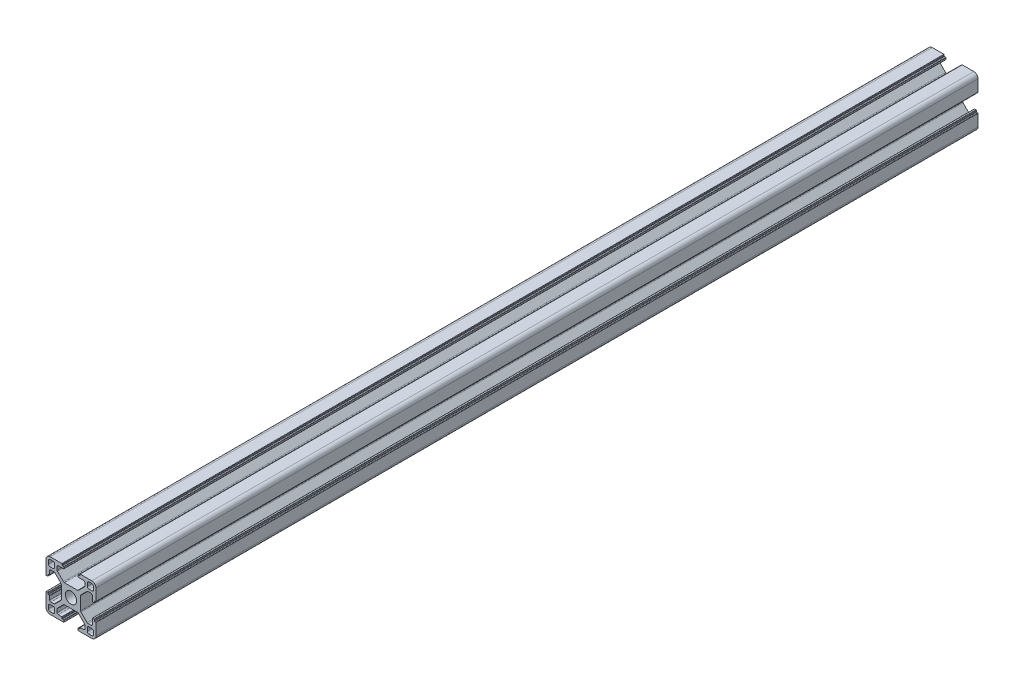
SolidWorks part; units mm, degrees
material "6063-T5"
ref_plane "Front Plane" through (0, 0, 0) normal (0, 0, 1) x (1, 0, 0)
ref_plane "Top Plane" through (0, 0, 0) normal (0, 1, 0) x (1, 0, 0)
ref_plane "Right Plane" through (0, 0, 0) normal (1, 0, 0) x (0, 0, -1)
sketch "Sketch1" plane through (0, 0, 0) normal (0, 0, 1) x (1, 0, 0)
  line L0 (0, 2.5) -> (0, 10.6)
  line L1 (2.5, 30) -> (9.5, 30)
  line L2 (30, 27.5) -> (30, 20.5)
  line L3 (27.5, 0) -> (19.4, 0)
  line L4 (19.464, 9.1128) -> (23.1303, 5.4465)
  line L5 (21.0197, 10.536) -> (24.686, 6.8697)
  line L6 (10.536, 21.0197) -> (6.8697, 24.686)
  line L7 (8.9803, 19.464) -> (5.314, 23.1303)
  line L8 (11.0663, 20.8) -> (18.9337, 20.8)
  line L9 (20.8, 18.9337) -> (20.8, 11.0663)
  line L10 (18.9337, 9.3324) -> (11.0663, 9.3324)
  line L11 (9.2, 11.0663) -> (9.2, 18.9337)
  line L12 (0, 19.4) -> (0, 27.5)
  line L13 (30, 9.5) -> (30, 2.5)
  line L14 (19.4, 27.8) -> (22.6, 27.8)
  line L15 (10.6, 27.8) -> (7.4, 27.8)
  line L16 (10.6, 0) -> (2.5, 0)
  line L17 (2.2, 20.5) -> (2.2, 22.6)
  line L18 (2.2, 9.5) -> (2.2, 7.4)
  line L19 (9.5, 2.3324) -> (7.4, 2.3324)
  line L20 (19.464, 21.0197) -> (23.1303, 24.686)
  line L21 (21.0197, 19.464) -> (24.686, 23.1303)
  line L22 (8.9803, 10.536) -> (5.314, 6.8697)
  line L23 (10.536, 9.1128) -> (6.8697, 5.4465)
  line L24 (10.8, 28.8) -> (10.8, 28)
  line L25 (19.2, 28.8) -> (19.2, 28)
  line L26 (0.2, 19.2) -> (1, 19.2)
  line L27 (0.2, 10.8) -> (1, 10.8)
  line L28 (28.8, 19.2) -> (28, 19.2)
  line L29 (28.8, 10.8) -> (28, 10.8)
  line L30 (10.8, 0.2) -> (10.8, 1.1324)
  line L31 (19.2, 0.2) -> (19.2, 1.1324)
  line L32 (20.5, 30) -> (27.5, 30)
  line L33 (27.8, 19.4) -> (27.8, 22.6)
  line L34 (27.8, 10.6) -> (27.8, 7.4)
  line L35 (20.5, 2.2) -> (22.6, 2.2)
  line L36 (6.65, 27.05) -> (6.65, 25.2163)
  line L37 (23.35, 27.05) -> (23.35, 25.2163)
  line L38 (2.95, 23.35) -> (4.7837, 23.35)
  line L39 (27.05, 23.35) -> (25.2163, 23.35)
  line L40 (2.95, 6.65) -> (4.7837, 6.65)
  line L41 (6.65, 3.0824) -> (6.65, 4.9161)
  line L42 (23.35, 2.95) -> (23.35, 4.9161)
  line L43 (27.05, 6.65) -> (25.2163, 6.65)
  line L44 (29, 10.6) -> (29, 9.9)
  line L45 (29.8, 20.3) -> (29.2, 20.3)
  line L46 (29, 20.1) -> (29, 19.4)
  line L47 (29.2, 9.7) -> (29.8, 9.7)
  line L48 (19.4, 29) -> (20.1, 29)
  line L49 (9.7, 29.8) -> (9.7, 29.2)
  line L50 (9.9, 29) -> (10.6, 29)
  line L51 (20.3, 29.2) -> (20.3, 29.8)
  line L52 (9.7, 2.1324) -> (9.7, 1.5324)
  line L53 (9.9, 1.3324) -> (10.6, 1.3324)
  line L54 (19.4, 1.3324) -> (20.1, 1.3324)
  line L55 (20.3, 1.5324) -> (20.3, 2)
  line L56 (2, 20.3) -> (1.4, 20.3)
  line L57 (1.2, 20.1) -> (1.2, 19.4)
  line L58 (1.2, 10.6) -> (1.2, 9.9)
  line L59 (1.4, 9.7) -> (2, 9.7)
  line L60 (27.55, 1.45) -> (25.8, 1.45)
  line L61 (24.8, 2.45) -> (24.8, 4.2)
  line L62 (25.8, 5.2) -> (27.55, 5.2)
  line L63 (28.55, 4.2) -> (28.55, 2.45)
  line L64 (24.8, 25.8) -> (24.8, 27.55)
  line L65 (25.8, 28.55) -> (27.55, 28.55)
  line L66 (28.55, 27.55) -> (28.55, 25.8)
  line L67 (27.55, 24.8) -> (25.8, 24.8)
  line L68 (2.45, 28.55) -> (4.2, 28.55)
  line L69 (5.2, 27.55) -> (5.2, 25.8)
  line L70 (1.45, 2.45) -> (1.45, 4.2)
  line L71 (2.45, 5.2) -> (4.2, 5.2)
  line L72 (5.2, 4.2) -> (5.2, 2.45)
  line L73 (4.2, 1.45) -> (2.45, 1.45)
  line L74 (4.2, 24.8) -> (2.45, 24.8)
  line L75 (1.45, 25.8) -> (1.45, 27.55)
  circle A0 centre (15, 15) radius 3.4
  arc A1 (25.8, 1.45) -> (24.8, 2.45) centre (25.8, 2.45) cw
  arc A2 (27.55, 1.45) -> (28.55, 2.45) centre (27.55, 2.45) ccw
  arc A3 (27.55, 5.2) -> (28.55, 4.2) centre (27.55, 4.2) cw
  arc A4 (24.8, 4.2) -> (25.8, 5.2) centre (25.8, 4.2) cw
  arc A5 (1.45, 2.45) -> (2.45, 1.45) centre (2.45, 2.45) ccw
  arc A6 (5.2, 2.45) -> (4.2, 1.45) centre (4.2, 2.45) cw
  arc A7 (4.2, 5.2) -> (5.2, 4.2) centre (4.2, 4.2) cw
  arc A8 (1.45, 4.2) -> (2.45, 5.2) centre (2.45, 4.2) cw
  arc A9 (24.8, 25.8) -> (25.8, 24.8) centre (25.8, 25.8) ccw
  arc A10 (28.55, 25.8) -> (27.55, 24.8) centre (27.55, 25.8) cw
  arc A11 (27.55, 28.55) -> (28.55, 27.55) centre (27.55, 27.55) cw
  arc A12 (24.8, 27.55) -> (25.8, 28.55) centre (25.8, 27.55) cw
  arc A13 (4.2, 28.55) -> (5.2, 27.55) centre (4.2, 27.55) cw
  arc A14 (5.2, 25.8) -> (4.2, 24.8) centre (4.2, 25.8) cw
  arc A15 (2.45, 24.8) -> (1.45, 25.8) centre (2.45, 25.8) cw
  arc A16 (2.45, 28.55) -> (1.45, 27.55) centre (2.45, 27.55) ccw
  arc A17 (30, 2.5) -> (27.5, 0) centre (27.5, 2.5) cw
  arc A18 (0, 2.5) -> (2.5, 0) centre (2.5, 2.5) ccw
  arc A19 (27.5, 30) -> (30, 27.5) centre (27.5, 27.5) cw
  arc A20 (0, 27.5) -> (2.5, 30) centre (2.5, 27.5) cw
  arc A21 (0, 10.6) -> (0.2, 10.8) centre (0.2, 10.6) cw
  arc A22 (1.2, 10.6) -> (1, 10.8) centre (1, 10.6) ccw
  arc A23 (2, 9.7) -> (2.2, 9.5) centre (2, 9.5) cw
  arc A24 (9.7, 2.1324) -> (9.5, 2.3324) centre (9.5, 2.1324) ccw
  arc A25 (10.6, 1.3324) -> (10.8, 1.1324) centre (10.6, 1.1324) cw
  arc A26 (10.6, 0) -> (10.8, 0.2) centre (10.6, 0.2) ccw
  arc A27 (19.4, 0) -> (19.2, 0.2) centre (19.4, 0.2) cw
  arc A28 (19.4, 1.3324) -> (19.2, 1.1324) centre (19.4, 1.1324) ccw
  arc A29 (20.3, 2) -> (20.5, 2.2) centre (20.5, 2) cw
  arc A30 (28, 10.8) -> (27.8, 10.6) centre (28, 10.6) ccw
  arc A31 (29, 10.6) -> (28.8, 10.8) centre (28.8, 10.6) ccw
  arc A32 (29.8, 9.7) -> (30, 9.5) centre (29.8, 9.5) cw
  arc A33 (28, 19.2) -> (27.8, 19.4) centre (28, 19.4) cw
  arc A34 (29, 19.4) -> (28.8, 19.2) centre (28.8, 19.4) cw
  arc A35 (30, 20.5) -> (29.8, 20.3) centre (29.8, 20.5) cw
  arc A36 (20.3, 29.8) -> (20.5, 30) centre (20.5, 29.8) cw
  arc A37 (19.4, 29) -> (19.2, 28.8) centre (19.4, 28.8) ccw
  arc A38 (19.2, 28) -> (19.4, 27.8) centre (19.4, 28) ccw
  arc A39 (10.8, 28) -> (10.6, 27.8) centre (10.6, 28) cw
  arc A40 (0, 19.4) -> (0.2, 19.2) centre (0.2, 19.4) ccw
  arc A41 (1.2, 19.4) -> (1, 19.2) centre (1, 19.4) cw
  arc A42 (2, 20.3) -> (2.2, 20.5) centre (2, 20.5) ccw
  arc A43 (10.6, 29) -> (10.8, 28.8) centre (10.6, 28.8) cw
  arc A44 (9.5, 30) -> (9.7, 29.8) centre (9.5, 29.8) cw
  arc A45 (1.4, 20.3) -> (1.2, 20.1) centre (1.4, 20.1) ccw
  arc A46 (20.1, 29) -> (20.3, 29.2) centre (20.1, 29.2) ccw
  arc A47 (9.7, 29.2) -> (9.9, 29) centre (9.9, 29.2) ccw
  arc A48 (29.2, 20.3) -> (29, 20.1) centre (29.2, 20.1) ccw
  arc A49 (29, 9.9) -> (29.2, 9.7) centre (29.2, 9.9) ccw
  arc A50 (20.1, 1.3324) -> (20.3, 1.5324) centre (20.1, 1.5324) ccw
  arc A51 (1.2, 9.9) -> (1.4, 9.7) centre (1.4, 9.9) ccw
  arc A52 (9.7, 1.5324) -> (9.9, 1.3324) centre (9.9, 1.5324) ccw
  arc A53 (23.35, 25.2163) -> (23.1303, 24.686) centre (22.6, 25.2163) cw
  arc A54 (25.2163, 23.35) -> (24.686, 23.1303) centre (25.2163, 22.6) ccw
  arc A55 (20.8, 18.9337) -> (21.0197, 19.464) centre (21.55, 18.9337) cw
  arc A56 (18.9337, 20.8) -> (19.464, 21.0197) centre (18.9337, 21.55) ccw
  arc A57 (6.65, 25.2163) -> (6.8697, 24.686) centre (7.4, 25.2163) ccw
  arc A58 (11.0663, 20.8) -> (10.536, 21.0197) centre (11.0663, 21.55) cw
  arc A59 (4.7837, 23.35) -> (5.314, 23.1303) centre (4.7837, 22.6) cw
  arc A60 (9.2, 18.9337) -> (8.9803, 19.464) centre (8.45, 18.9337) ccw
  arc A61 (4.7837, 6.65) -> (5.314, 6.8697) centre (4.7837, 7.4) ccw
  arc A62 (9.2, 11.0663) -> (8.9803, 10.536) centre (8.45, 11.0663) cw
  arc A63 (6.65, 4.9161) -> (6.8697, 5.4465) centre (7.4, 4.9161) cw
  arc A64 (11.0663, 9.3324) -> (10.536, 9.1128) centre (11.0663, 8.5824) ccw
  arc A65 (18.9337, 9.3324) -> (19.464, 9.1128) centre (18.9337, 8.5824) cw
  arc A66 (20.8, 11.0663) -> (21.0197, 10.536) centre (21.55, 11.0663) ccw
  arc A67 (25.2163, 6.65) -> (24.686, 6.8697) centre (25.2163, 7.4) cw
  arc A68 (23.35, 4.9161) -> (23.1303, 5.4465) centre (22.6, 4.9161) ccw
  arc A69 (7.4, 2.3324) -> (6.65, 3.0824) centre (7.4, 3.0824) cw
  arc A70 (22.6, 2.2) -> (23.35, 2.95) centre (22.6, 2.95) ccw
  arc A71 (27.8, 7.4) -> (27.05, 6.65) centre (27.05, 7.4) cw
  arc A72 (27.8, 22.6) -> (27.05, 23.35) centre (27.05, 22.6) ccw
  arc A73 (22.6, 27.8) -> (23.35, 27.05) centre (22.6, 27.05) cw
  arc A74 (2.2, 7.4) -> (2.95, 6.65) centre (2.95, 7.4) ccw
  arc A75 (2.2, 22.6) -> (2.95, 23.35) centre (2.95, 22.6) cw
  arc A76 (7.4, 27.8) -> (6.65, 27.05) centre (7.4, 27.05) ccw
  point P115 (0, 0)
extrude "Boss-Extrude1" add sketch "Sketch1" along normal blind 530
